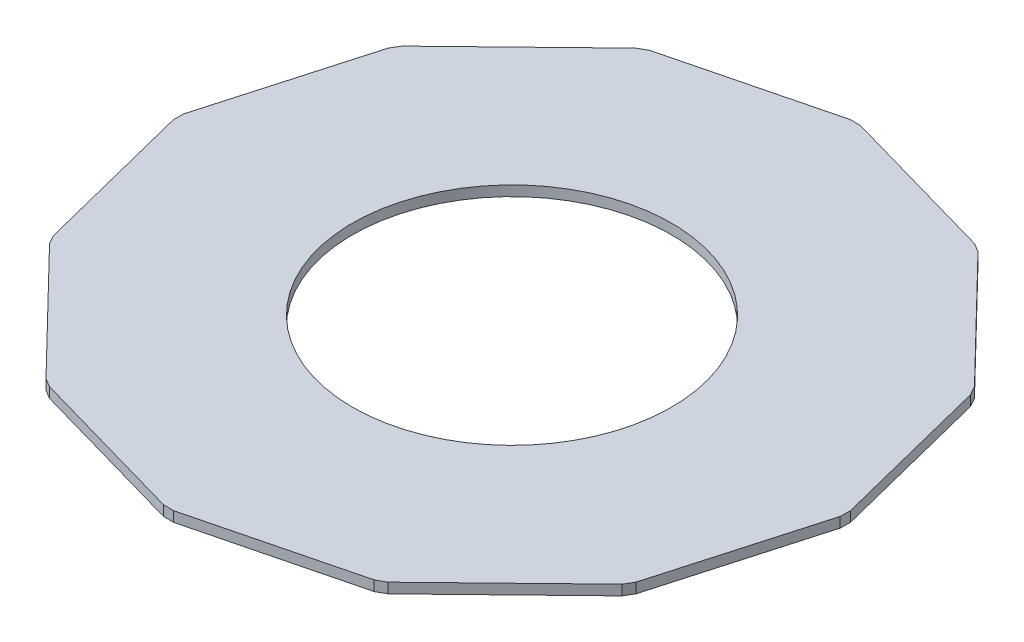
SolidWorks part; units mm, degrees
ref_plane "Front Plane" through (0, 0, 0) normal (0, 0, 1) x (1, 0, 0)
ref_plane "Top Plane" through (0, 0, 0) normal (0, 1, 0) x (1, 0, 0)
ref_plane "Right Plane" through (0, 0, 0) normal (1, 0, 0) x (0, 0, -1)
sketch "Sketch1" plane through (0, 0, 0) normal (0, 1, 0) x (1, 0, 0)
  line L0 (-88.0682, -47.3709) -> (-100, 0.01)
  line L1 (-100, 0.01) -> (-99.9547, 3.0097)
  line L2 (-99.9547, 3.0097) -> (-86.5975, 50.0087)
  line L3 (-86.5975, 50.0087) -> (-85.0585, 52.5838)
  line L4 (-85.0585, 52.5838) -> (-49.9913, 86.6076)
  line L5 (-49.9913, 86.6076) -> (-47.3709, 88.0682)
  line L6 (-47.3709, 88.0682) -> (0.01, 100)
  line L7 (0.01, 100) -> (3.0097, 99.9547)
  line L8 (3.0097, 99.9547) -> (50.0087, 86.5975)
  line L9 (50.0087, 86.5975) -> (52.5838, 85.0585)
  line L10 (52.5838, 85.0585) -> (86.6076, 49.9913)
  line L11 (86.6076, 49.9913) -> (88.0682, 47.3709)
  line L12 (88.0682, 47.3709) -> (100, -0.01)
  line L13 (100, -0.01) -> (99.9547, -3.0097)
  line L14 (99.9547, -3.0097) -> (86.5975, -50.0087)
  line L15 (86.5975, -50.0087) -> (85.0585, -52.5838)
  line L16 (85.0585, -52.5838) -> (49.9913, -86.6076)
  line L17 (49.9913, -86.6076) -> (47.3709, -88.0682)
  line L18 (47.3709, -88.0682) -> (-0.01, -100)
  line L19 (-0.01, -100) -> (-3.0097, -99.9547)
  line L20 (-3.0097, -99.9547) -> (-50.0087, -86.5975)
  line L21 (-50.0087, -86.5975) -> (-52.5838, -85.0585)
  line L22 (-52.5838, -85.0585) -> (-86.6076, -49.9913)
  line L23 (-86.6076, -49.9913) -> (-88.0682, -47.3709)
  arc A0 (-88.0682, -47.3709) -> (-99.9547, 3.0097) centre (0, 0) cw construction
  arc A1 (-99.9547, 3.0097) -> (-85.0585, 52.5838) centre (0, 0) cw construction
  arc A2 (-85.0585, 52.5838) -> (-47.3709, 88.0682) centre (0, 0) cw construction
  arc A3 (-47.3709, 88.0682) -> (3.0097, 99.9547) centre (0, 0) cw construction
  arc A4 (3.0097, 99.9547) -> (52.5838, 85.0585) centre (0, 0) cw construction
  arc A5 (52.5838, 85.0585) -> (88.0682, 47.3709) centre (0, 0) cw construction
  arc A6 (88.0682, 47.3709) -> (99.9547, -3.0097) centre (0, 0) cw construction
  arc A7 (99.9547, -3.0097) -> (85.0585, -52.5838) centre (0, 0) cw construction
  arc A8 (85.0585, -52.5838) -> (47.3709, -88.0682) centre (0, 0) cw construction
  arc A9 (47.3709, -88.0682) -> (-3.0097, -99.9547) centre (0, 0) cw construction
  arc A10 (-3.0097, -99.9547) -> (-52.5838, -85.0585) centre (0, 0) cw construction
  arc A11 (-52.5838, -85.0585) -> (-88.0682, -47.3709) centre (0, 0) cw construction
  circle A12 centre (0, 0) radius 47.1167
  point P41 (0, 0)
  dimension "D1" = 12
extrude "Boss-Extrude1" add sketch "Sketch1" along normal blind 3
